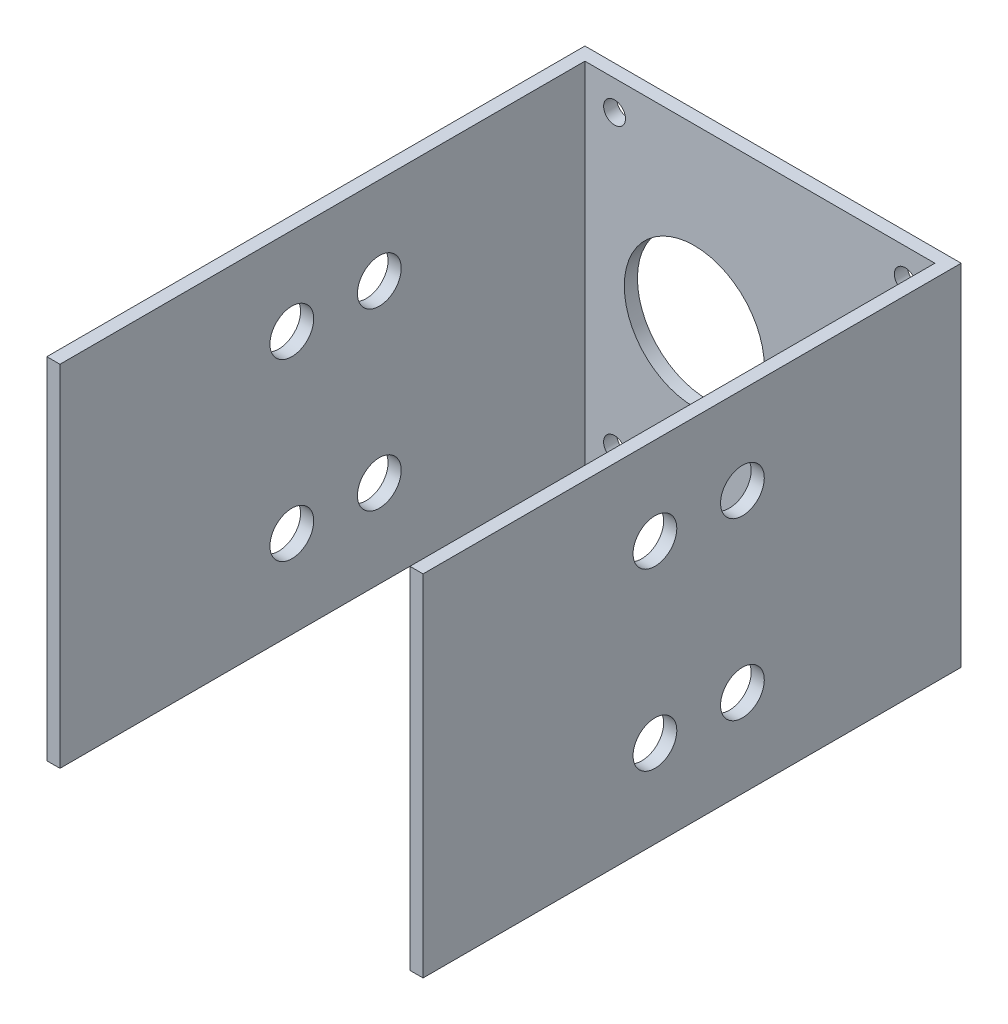
SolidWorks part; units mm, degrees
ref_plane "Front Plane" through (0, 0, 0) normal (0, 0, 1) x (1, 0, 0)
ref_plane "Top Plane" through (0, 0, 0) normal (0, 1, 0) x (1, 0, 0)
ref_plane "Right Plane" through (0, 0, 0) normal (1, 0, 0) x (0, 0, -1)
sketch "Sketch1" plane through (0, 0, 0) normal (0, 0, 1) x (1, 0, 0)
  line L1 (-43, 40) -> (43, 40)
  line L2 (-43, 40) -> (-43, -40)
  line L3 (-43, -40) -> (43, -40)
  line L4 (43, 40) -> (43, -40)
  line L5 (-43, 40) -> (43, -40) construction
  line L6 (-43, -40) -> (43, 40) construction
  point P0 (0, 0)
  dimension "D1" = 86
  dimension "D2" = 80
extrude "Boss-Extrude1" add sketch "Sketch1" along normal blind 3
sketch "Sketch2" plane through (0, 0, 3) normal (0, 0, 1) x (1, 0, 0)
  line L0 (-43, 40) -> (-40, 40)
  line L1 (43, 40) -> (-43, 40) construction
  line L2 (-40, 40) -> (-40, -40)
  line L3 (-43, -40) -> (43, -40) construction
  line L4 (-40, -40) -> (-43, -40)
  line L5 (-43, -40) -> (-43, 40)
  line L6 (43, 40) -> (40, 40)
  line L7 (40, 40) -> (40, -40)
  line L8 (40, -40) -> (43, -40)
  line L9 (43, -40) -> (43, 40)
  dimension "D1" = 3
  dimension "D2" = 3
extrude "Boss-Extrude2" add sketch "Sketch2" along normal blind 120 contours L5 L0 L2 L4 | L9 L6 L7 L8
sketch "Sketch3" plane through (0, 0, 0) normal (0, 0, -1) x (-1, 0, 0)
  line L1 (43, -40) -> (-43, -40) construction
  line L3 (43, 40) -> (43, -40) construction
  circle A0 centre (15, 0) radius 16
  dimension "D1" = 32
  dimension "D2" = 28
  dimension "D3" = 40
extrude "Cut-Extrude1" cut sketch "Sketch3" against normal blind 120
sketch "Sketch4" plane through (0, 0, 0) normal (0, 0, -1) x (-1, 0, 0)
  line L0 (-43, -40) -> (-43, 40) construction
  line L1 (-43, 40) -> (43, 40) construction
  line L2 (43, 40) -> (43, -40) construction
  line L3 (43, -40) -> (-43, -40) construction
  circle A0 centre (-33.23, 33.23) radius 2.5
  circle A1 centre (-33.23, -33.23) radius 2.5
  circle A2 centre (33.23, -33.23) radius 2.5
  circle A3 centre (33.23, 33.23) radius 2.5
  dimension "D1" = 5
  dimension "D2" = 9.77
  dimension "D3" = 6.77
  dimension "D4" = 9.77
  dimension "D5" = 9.77
  dimension "D6" = 9.77
  dimension "D7" = 6.77
  dimension "D8" = 6.77
  dimension "D9" = 6.77
extrude "Cut-Extrude2" cut sketch "Sketch4" against normal blind 120
sketch "Sketch5" plane through (43, 0, 0) normal (1, 0, 0) x (0, 0, -1)
  line L1 (-123, 40) -> (0, 40) construction
  line L2 (0, -40) -> (0, 40) construction
  circle A0 centre (-50, 20) radius 5
  circle A1 centre (-50, -20) radius 5
  circle A2 centre (-70, 20) radius 5
  circle A3 centre (-70, -20) radius 5
  dimension "D1" = 10
  dimension "D2" = 20
  dimension "D3" = 20
  dimension "D4" = 50
  dimension "D6" = 40
  dimension "D7" = 20
extrude "Cut-Extrude3" cut sketch "Sketch5" against normal through all
